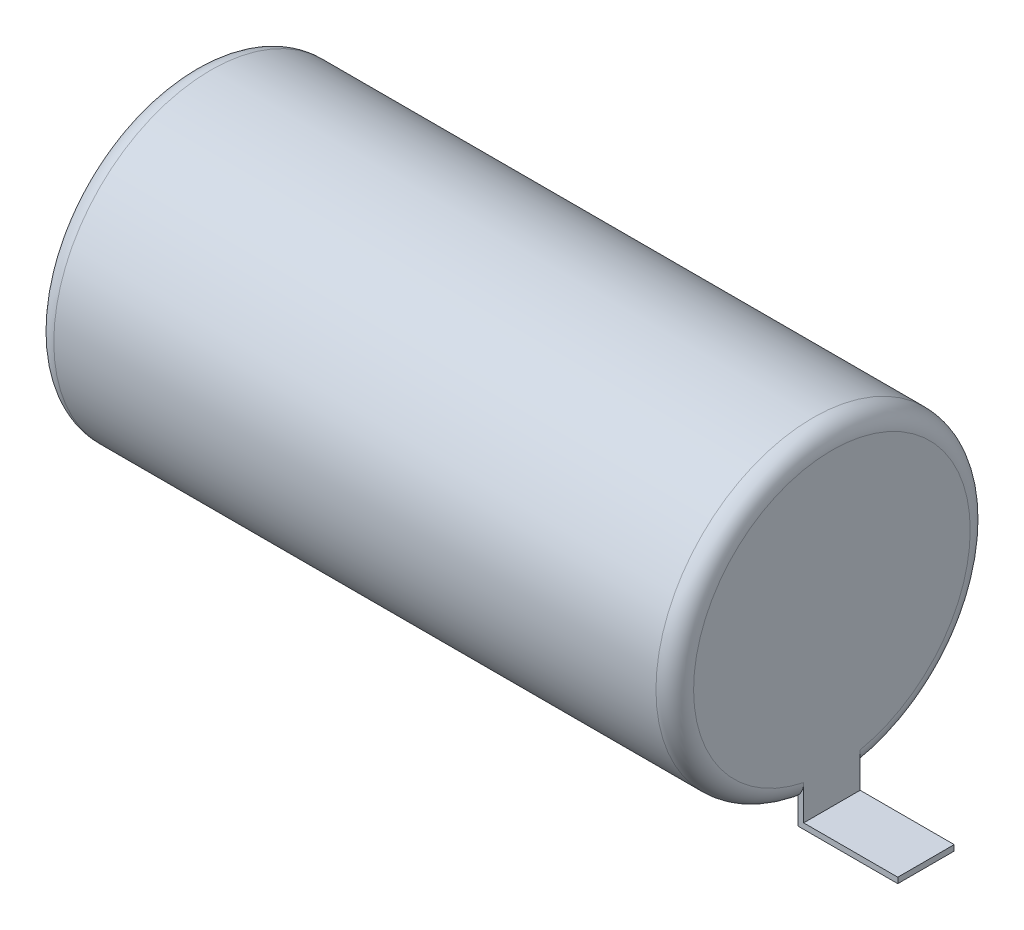
SolidWorks part; units mm, degrees
ref_plane "Спереди" through (0, 0, 0) normal (0, 0, 1) x (1, 0, 0)
ref_plane "Сверху" through (0, 0, 0) normal (0, 1, 0) x (1, 0, 0)
ref_plane "Справа" through (0, 0, 0) normal (1, 0, 0) x (0, 0, -1)
sketch "Эскиз1" plane through (0, 0, 0) normal (1, 0, 0) x (0, 0, -1)
  circle A1 centre (0, 0) radius 8.35
  dimension "D1" = 16.7
extrude "Бобышка-Вытянуть1" add sketch "Эскиз1" along normal mid plane 34
fillet "Скругление1" radius 1 2 edges at (-17, 0, -8.35) (17, 0, -8.35)
sketch "Эскиз2" plane through (17, 0, 0) normal (1, 0, 0) x (0, 0, -1)
  line L0 (0, -1000) -> (0, 49000) construction
  line L1 (-1.5, -7.1953) -> (0, -7.1953) construction
  line L8 (-1.5, -9.35) -> (1.5, -9.35)
  line L9 (-1.5, -9.35) -> (-1.5, -7.1953)
  line L10 (0, -7.1953) -> (1.5, -7.1953) construction
  line L11 (1.5, -9.35) -> (1.5, -7.1953)
  line L12 (-1.5, -9.35) -> (1.5, -7.1953) construction
  line L13 (-1.5, -7.1953) -> (1.5, -9.35) construction
  circle A0 centre (0, 0) radius 7.35 construction
  arc A2 (1.5, -7.1953) -> (0, 7.35) centre (0, 0) ccw construction
  arc A3 (-1.5, -7.1953) -> (1.5, -7.1953) centre (0, 0) ccw
  arc A4 (0, 7.35) -> (-1.5, -7.1953) centre (0, 0) ccw construction
  circle A5 centre (0, 0) radius 8.35 construction
  circle A6 centre (0, 0) radius 8.35 construction
  point P5 (0, -8.2727)
  point P15 (0, -8.35)
  dimension "D1" = 3
  dimension "D2" = 1
extrude "Бобышка-Вытянуть2" add sketch "Эскиз2" against normal blind 0.3
sketch "Эскиз3" plane through (17, 0, 0) normal (1, 0, 0) x (0, 0, -1)
  line L0 (1.5, -9.35) -> (1.5, -7.1953) construction
  line L1 (-1.5, -7.1953) -> (-1.5, -9.35) construction
  line L2 (-1.5, -9.35) -> (1.5, -9.35) construction
  line L3 (1.5, -9.35) -> (1.5, -9.05)
  line L4 (-1.5, -9.05) -> (-1.5, -9.35)
  line L5 (-1.5, -9.35) -> (1.5, -9.35)
  line L6 (-1.5, -9.05) -> (1.5, -9.05)
  line L7 (-1.5, -7.1953) -> (-1.5, -9.05) construction
  line L8 (1.5, -9.05) -> (1.5, -7.1953) construction
  dimension "D1" = 0.3
extrude "Бобышка-Вытянуть3" add sketch "Эскиз3" along normal blind 5
mirror "Зеркальное отражение1" about plane through (0, 0, 0) normal (1, 0, 0) of "Бобышка-Вытянуть3", "Бобышка-Вытянуть2"
